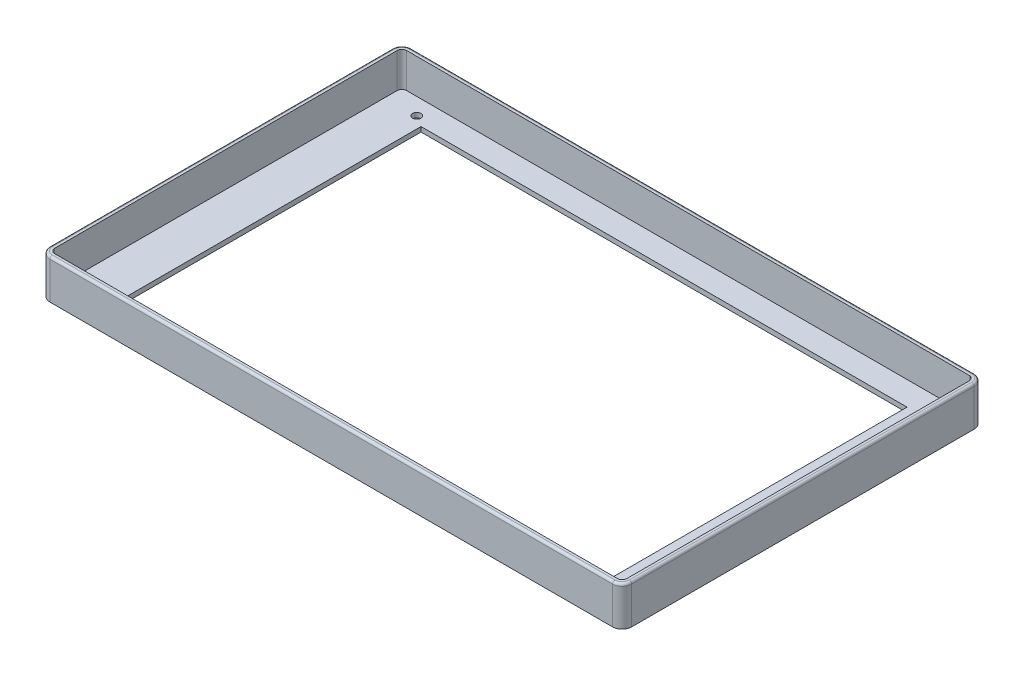
SolidWorks part; units mm, degrees
ref_plane "Ebene vorne" through (0, 0, 0) normal (0, 0, 1) x (1, 0, 0)
ref_plane "Ebene oben" through (0, 0, 0) normal (0, 1, 0) x (1, 0, 0)
ref_plane "Ebene rechts" through (0, 0, 0) normal (1, 0, 0) x (0, 0, -1)
sketch "Skizze1" plane through (0, 0, 0) normal (0, 1, 0) x (1, 0, 0)
  line L1 (0, 0) -> (243, 0)
  line L2 (0, 0) -> (0, 151)
  line L3 (0, 151) -> (243, 151)
  line L4 (243, 0) -> (243, 151)
  line L5 (20, 14) -> (223, 14)
  line L6 (20, 14) -> (20, 139)
  line L7 (20, 139) -> (223, 139)
  line L8 (223, 14) -> (223, 139)
  dimension "D1" = 203
  dimension "D2" = 20
  dimension "D3" = 20
  dimension "D4" = 14
  dimension "D5" = 12
  dimension "D6" = 125
extrude "Aufsatz-Linear austragen1" add sketch "Skizze1" along normal blind 2
sketch "Skizze2" plane through (0, 2, 0) normal (0, 1, 0) x (1, 0, 0)
  line L1 (0, 0) -> (243, 0)
  line L2 (0, 0) -> (0, 151)
  line L3 (0, 151) -> (243, 151)
  line L4 (243, 0) -> (243, 151)
  line L5 (2, 2) -> (241, 2)
  line L6 (2, 2) -> (2, 149)
  line L7 (2, 149) -> (241, 149)
  line L8 (241, 2) -> (241, 149)
  dimension "D1" = 2
  dimension "D2" = 2
  dimension "D3" = 2
  dimension "D4" = 2
extrude "Aufsatz-Linear austragen2" add sketch "Skizze2" along normal blind 14.5
sketch "Skizze3" plane through (0, 2, 0) normal (0, 1, 0) x (1, 0, 0)
  line L0 (2, 149) -> (2, 2) construction
  line L1 (241, 149) -> (2, 149) construction
  line L2 (241, 2) -> (241, 149) construction
  line L3 (2, 2) -> (241, 2) construction
  circle A0 centre (15.23, 142) radius 1.75
  circle A1 centre (233.33, 142) radius 1.75
  circle A2 centre (15.23, 9) radius 1.75
  circle A3 centre (233.33, 9) radius 1.75
  dimension "D1" = 3.5
  dimension "D2" = 13.23
  dimension "D3" = 7
  dimension "D4" = 7.67
  dimension "D5" = 7
extrude "Schnitt-Linear austragen1" cut sketch "Skizze3" against normal through all
fillet "Verrundung1" radius 2 4 edges at (2, 9.25, -2) (241, 9.25, -2) (241, 9.25, -149) (2, 9.25, -149)
fillet "Verrundung2" radius 4 4 edges at (0, 8.25, -151) (243, 8.25, -151) (243, 8.25, 0) (0, 8.25, 0)
fillet "Verrundung3" radius 1 8 edges at (1.1716, 16.5, -1.1716) (0, 16.5, -75.5) (1.1716, 16.5, -149.8284) (121.5, 16.5, -151) (241.8284, 16.5, -149.8284) (243, 16.5, -75.5) (241.8284, 16.5, -1.1716) (121.5, 16.5, 0)
